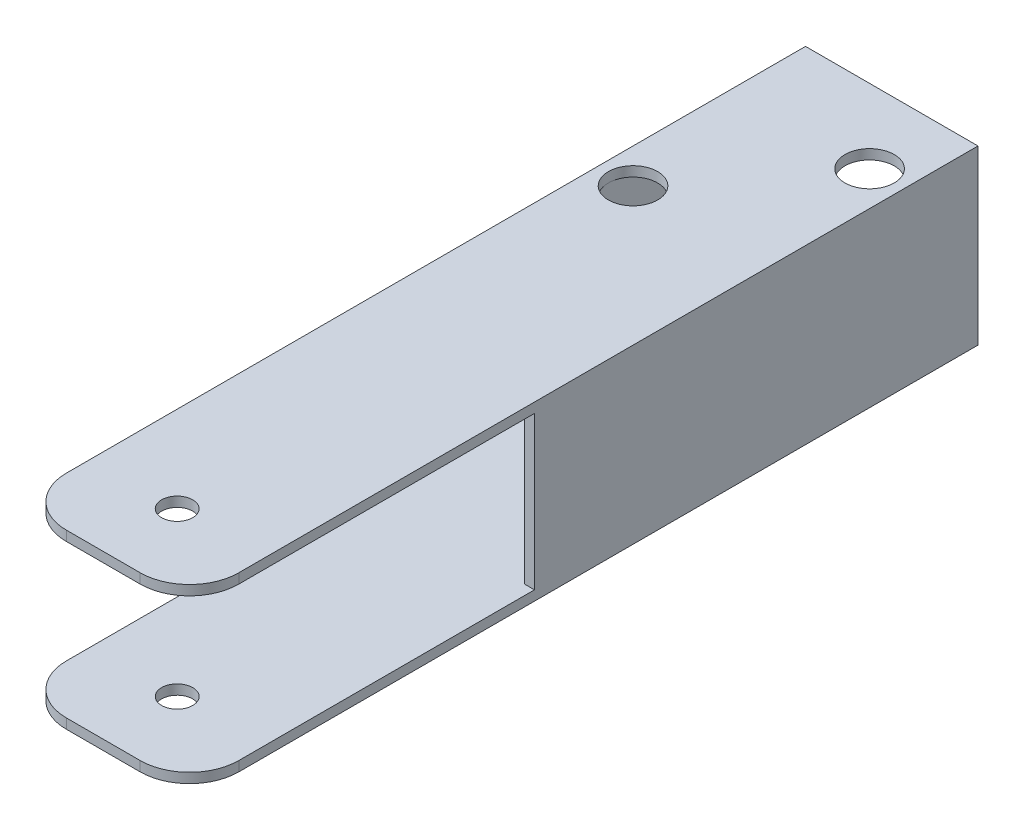
SolidWorks part; units mm, degrees
material "6061 Legierung"
ref_plane "Ebene vorne" through (0, 0, 0) normal (0, 0, 1) x (1, 0, 0)
ref_plane "Ebene oben" through (0, 0, 0) normal (0, 1, 0) x (1, 0, 0)
ref_plane "Ebene rechts" through (0, 0, 0) normal (1, 0, 0) x (0, 0, -1)
sketch "Skizze1" plane through (0, 0, 0) normal (0, 0, 1) x (1, 0, 0)
  line L1 (-17.5, -17.5) -> (17.5, -17.5)
  line L2 (-17.5, -17.5) -> (-17.5, 17.5)
  line L3 (-17.5, 17.5) -> (17.5, 17.5)
  line L4 (17.5, -17.5) -> (17.5, 17.5)
  line L5 (-17.5, -17.5) -> (17.5, 17.5) construction
  line L6 (-17.5, 17.5) -> (17.5, -17.5) construction
  line L7 (-15.5, -15.5) -> (15.5, -15.5)
  line L8 (-15.5, -15.5) -> (-15.5, 15.5)
  line L9 (-15.5, 15.5) -> (15.5, 15.5)
  line L10 (15.5, -15.5) -> (15.5, 15.5)
  line L11 (-15.5, -15.5) -> (15.5, 15.5) construction
  line L12 (-15.5, 15.5) -> (15.5, -15.5) construction
  point P0 (0, 0)
  point P6 (0, 0)
  dimension "D1" = 35
  dimension "D2" = 35
  dimension "D3" = 31
extrude "Aufsatz-Linear austragen1" add sketch "Skizze1" along normal blind 185
sketch "Skizze6" plane through (17.5, 0, 0) normal (1, 0, 0) x (0, 0, -1)
  line L0 (-185, 17.5) -> (0, 17.5) construction
  line L1 (-185, -15.5) -> (-115, -15.5)
  line L2 (-185, -15.5) -> (-185, 15.5)
  line L3 (-185, 15.5) -> (-115, 15.5)
  line L4 (-115, -15.5) -> (-115, 15.5)
  dimension "D1" = 2
  dimension "D2" = 70
extrude "Schnitt-Linear austragen1" cut sketch "Skizze6" against normal through all
sketch "Skizze7" plane through (0, -17.5, 0) normal (0, -1, 0) x (1, 0, 0)
  line L0 (-17.5, 185) -> (17.5, 185) construction
  circle A0 centre (0, 170) radius 3.15
  dimension "D1" = 6.3
  dimension "D2" = 15
extrude "Schnitt-Linear austragen2" cut sketch "Skizze7" against normal through all
fillet "Verrundung1" radius 10 4 edges at (17.5, 16.5, 185) (-17.5, 16.5, 185) (-17.5, -16.5, 185) (17.5, -16.5, 185)
sketch "Skizze10" plane through (0, 0, 0) normal (0, 0, -1) x (-1, 0, 0)
  line L1 (-19.6655, -18.5128) -> (19.6655, -18.5128)
  line L2 (-19.6655, -18.5128) -> (-19.6655, 18.5128)
  line L3 (-19.6655, 18.5128) -> (19.6655, 18.5128)
  line L4 (19.6655, -18.5128) -> (19.6655, 18.5128)
  line L5 (-19.6655, -18.5128) -> (19.6655, 18.5128) construction
  line L6 (-19.6655, 18.5128) -> (19.6655, -18.5128) construction
  point P0 (0, 0)
extrude "Schnitt-Linear austragen3" cut sketch "Skizze10" against normal blind 25
sketch "Skizze11" plane through (0, 17.5, 0) normal (0, 1, 0) x (1, 0, 0)
  line L1 (17.5, -25) -> (-17.5, -25) construction
  line L2 (17.5, -175) -> (17.5, -25) construction
  line L3 (-17.5, -175) -> (-17.5, -25) construction
  circle A0 centre (10.5, -40) radius 5
  circle A1 centre (-10.5, -67) radius 5
  dimension "D1" = 15
  dimension "D2" = 10
  dimension "D5" = 10
  dimension "D3" = 7
  dimension "D4" = 42
  dimension "D6" = 7
extrude "Schnitt-Linear austragen4" cut sketch "Skizze11" against normal through all
